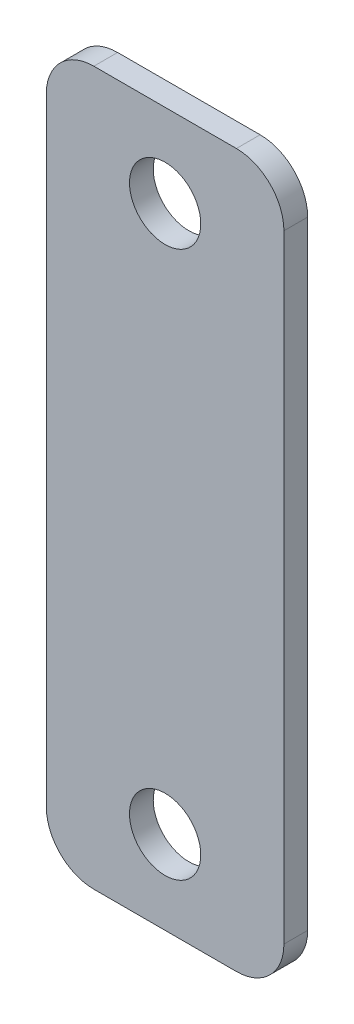
SolidWorks part; units mm, degrees
material "Thornel Mat VMA"
ref_plane "前视基准面" through (0, 0, 0) normal (0, 0, 1) x (1, 0, 0)
ref_plane "上视基准面" through (0, 0, 0) normal (0, 1, 0) x (1, 0, 0)
ref_plane "右视基准面" through (0, 0, 0) normal (1, 0, 0) x (0, 0, -1)
sketch "草图1" plane through (0, 0, 0) normal (0, 0, 1) x (1, 0, 0)
  line L1 (-5, -15) -> (5, -15)
  line L2 (-5, -15) -> (-5, 15)
  line L3 (-5, 15) -> (5, 15)
  line L4 (5, -15) -> (5, 15)
  line L5 (-5, -15) -> (5, 15) construction
  line L6 (-5, 15) -> (5, -15) construction
  point P0 (0, 0)
  dimension "D1" = 30
  dimension "D2" = 10
extrude "凸台-拉伸1" add sketch "草图1" along normal mid plane 1
sketch "草图2" plane through (0, 0, 0.5) normal (0, 0, 1) x (1, 0, 0)
  line L0 (0, -11.5) -> (0, 11.5) construction
  circle A0 centre (0, 11.5) radius 1.5
  circle A1 centre (0, -11.5) radius 1.5
  point P4 (0, 0)
  dimension "D2" = 3
  dimension "D1" = 23
extrude "切除-拉伸1" cut sketch "草图2" against normal blind 10
fillet "圆角1" radius 2 4 edges at (5, -15, 0) (-5, -15, 0) (-5, 15, 0) (5, 15, 0)
